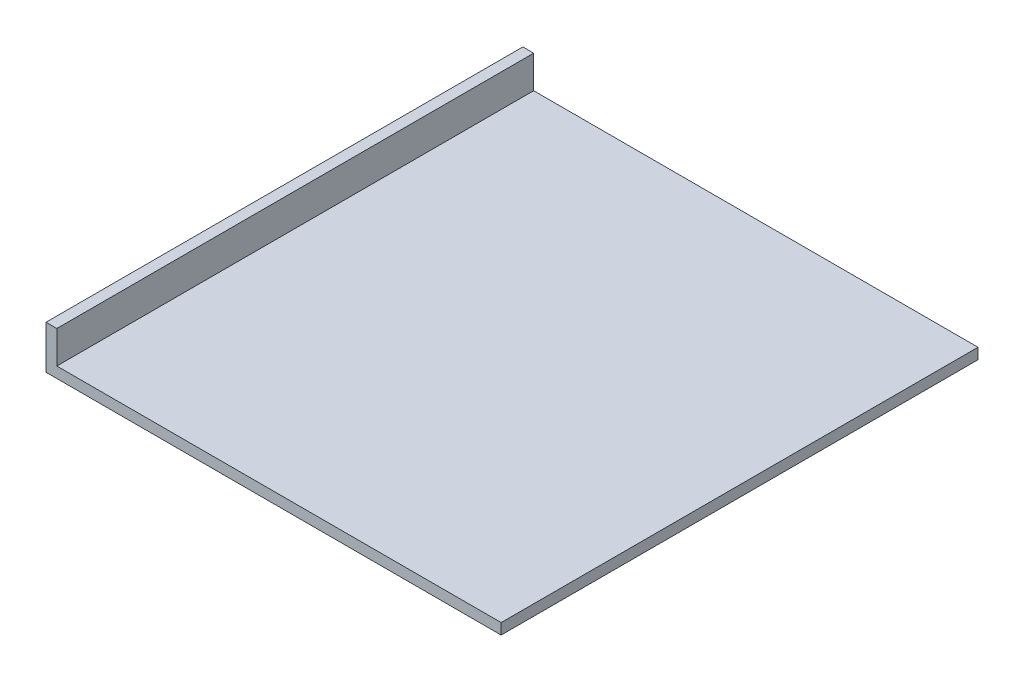
SolidWorks part; units mm, degrees
ref_plane "Front Plane" through (0, 0, 0) normal (0, 0, 1) x (1, 0, 0)
ref_plane "Top Plane" through (0, 0, 0) normal (0, 1, 0) x (1, 0, 0)
ref_plane "Right Plane" through (0, 0, 0) normal (1, 0, 0) x (0, 0, -1)
sketch "Sketch1" plane through (0, 0, 0) normal (0, 1, 0) x (1, 0, 0)
  line L1 (-105, -110) -> (105, -110)
  line L2 (-105, -110) -> (-105, 110)
  line L3 (-105, 110) -> (105, 110)
  line L4 (105, -110) -> (105, 110)
  line L5 (-105, -110) -> (105, 110) construction
  line L6 (-105, 110) -> (105, -110) construction
  point P0 (0, 0)
  dimension "D1" = 210
  dimension "D2" = 220
extrude "Boss-Extrude1" add sketch "Sketch1" along normal blind 5
sketch "Sketch2" plane through (0, 5, 0) normal (0, 1, 0) x (1, 0, 0)
  line L0 (-105, -110) -> (105, -110) construction
  line L1 (-105, 110) -> (-100, 110)
  line L2 (-105, 110) -> (-105, -110)
  line L3 (-105, -110) -> (-100, -110)
  line L4 (-100, 110) -> (-100, -110)
  dimension "D1" = 5
extrude "Boss-Extrude3" add sketch "Sketch2" along normal blind 15
sketch "Sketch3" plane through (0, 0, -110) normal (0, 0, -1) x (-1, 0, 0)
  line L0 (-105, 5) -> (-115.2936, 0)
  line L1 (115.5, 0) -> (-115.5, 0) construction
